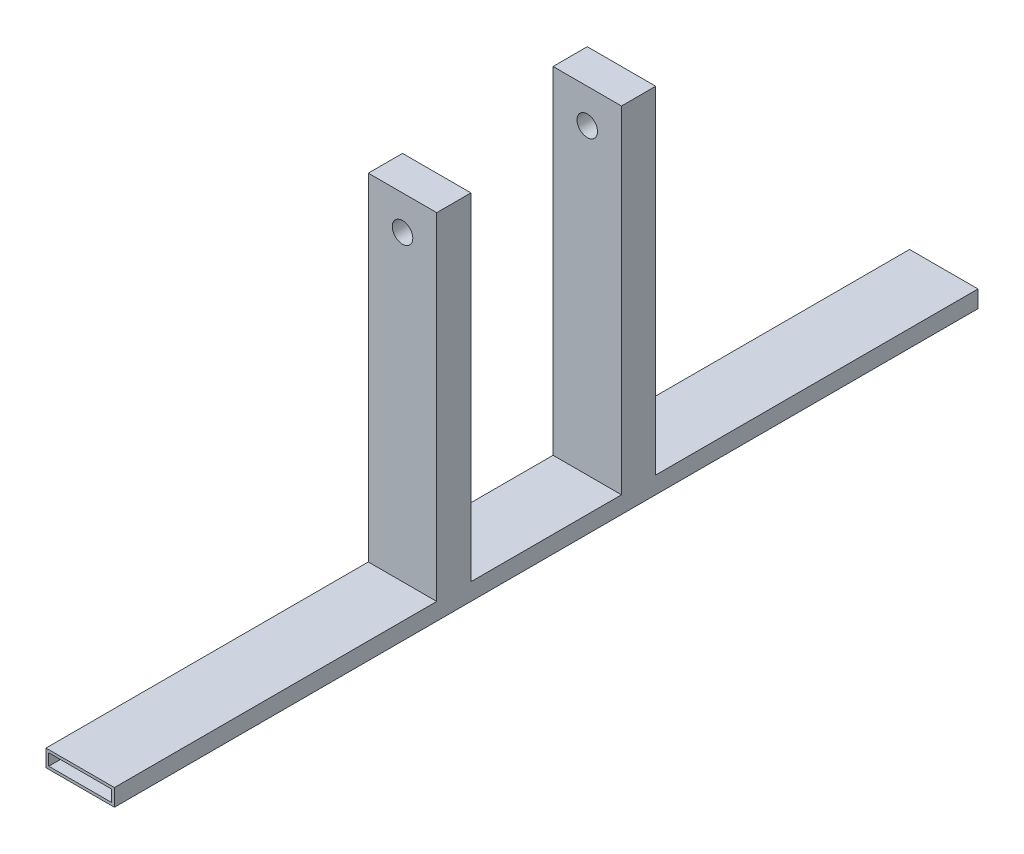
SolidWorks part; units mm, degrees
ref_plane "Front Plane" through (0, 0, 0) normal (0, 0, 1) x (1, 0, 0)
ref_plane "Top Plane" through (0, 0, 0) normal (0, 1, 0) x (1, 0, 0)
ref_plane "Right Plane" through (0, 0, 0) normal (1, 0, 0) x (0, 0, -1)
sketch "Sketch1" plane through (0, 0, 0) normal (0, 0, 1) x (1, 0, 0)
  line L1 (-16.6041, 3.9583) -> (33.3959, 3.9583)
  line L2 (-16.6041, 3.9583) -> (-16.6041, -8.5417)
  line L3 (-16.6041, -8.5417) -> (33.3959, -8.5417)
  line L4 (33.3959, 3.9583) -> (33.3959, -8.5417)
  dimension "D1" = 50
  dimension "D2" = 12.5
extrude "Boss-Extrude1" add sketch "Sketch1" along normal blind 631
shell "Shell1" thickness 2
sketch "Sketch3" plane through (0, 0, 0) normal (0, 1, 0) x (1, 0, 0)
  line L0 (-16.6041, -631) -> (-16.6041, 0) construction
  line L1 (-16.6041, -235.5) -> (33.3959, -235.5)
  line L2 (-16.6041, -235.5) -> (-16.6041, -260.5)
  line L3 (-16.6041, -260.5) -> (33.3959, -260.5)
  line L4 (33.3959, -235.5) -> (33.3959, -260.5)
  line L5 (33.3959, -631) -> (33.3959, 0) construction
  line L6 (-16.6041, -395.5) -> (33.3959, -395.5)
  line L7 (-16.6041, -370.5) -> (33.3959, -370.5)
  line L8 (-16.6041, -370.5) -> (-16.6041, -395.5)
  line L9 (33.3959, -370.5) -> (33.3959, -395.5)
  line L10 (-16.6041, 0) -> (33.3959, 0) construction
  line L11 (-16.6041, -631) -> (33.3959, -631) construction
  dimension "D1" = 25
  dimension "D3" = 110
  dimension "D4" = 235.5
  dimension "D5" = 235.5
  dimension "D2" = 2
extrude "Boss-Extrude2" add sketch "Sketch3" along normal blind 250
sketch "Sketch4" plane through (0, 0, 235.5) normal (0, 0, -1) x (-1, 0, 0)
  line L0 (16.6041, 250) -> (16.6041, 3.9583) construction
  line L1 (-33.3959, 250) -> (16.6041, 250) construction
  circle A0 centre (-8.3959, 225) radius 7.5
  point P6 (0, 0)
  dimension "D1" = 25
  dimension "D2" = 25
extrude "Cut-Extrude1" cut sketch "Sketch4" against normal through all both and the other way through all
